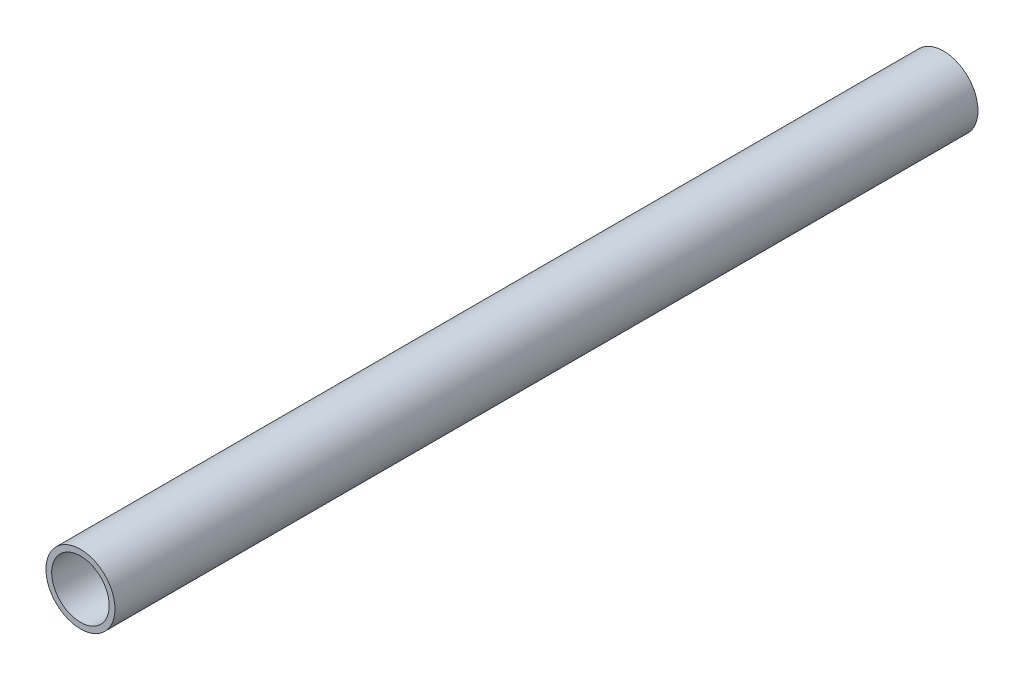
SolidWorks part; units mm, degrees
ref_plane "前视基准面" through (0, 0, 0) normal (0, 0, 1) x (1, 0, 0)
ref_plane "上视基准面" through (0, 0, 0) normal (0, 1, 0) x (1, 0, 0)
ref_plane "右视基准面" through (0, 0, 0) normal (1, 0, 0) x (0, 0, -1)
sketch "草图1" plane through (0, 0, 0) normal (0, 0, 1) x (1, 0, 0)
  circle A0 centre (0, 0) radius 5
  circle A1 centre (0, 0) radius 6
  dimension "D1" = 10
  dimension "D2" = 12
extrude "凸台-拉伸1" add sketch "草图1" along normal blind 150
